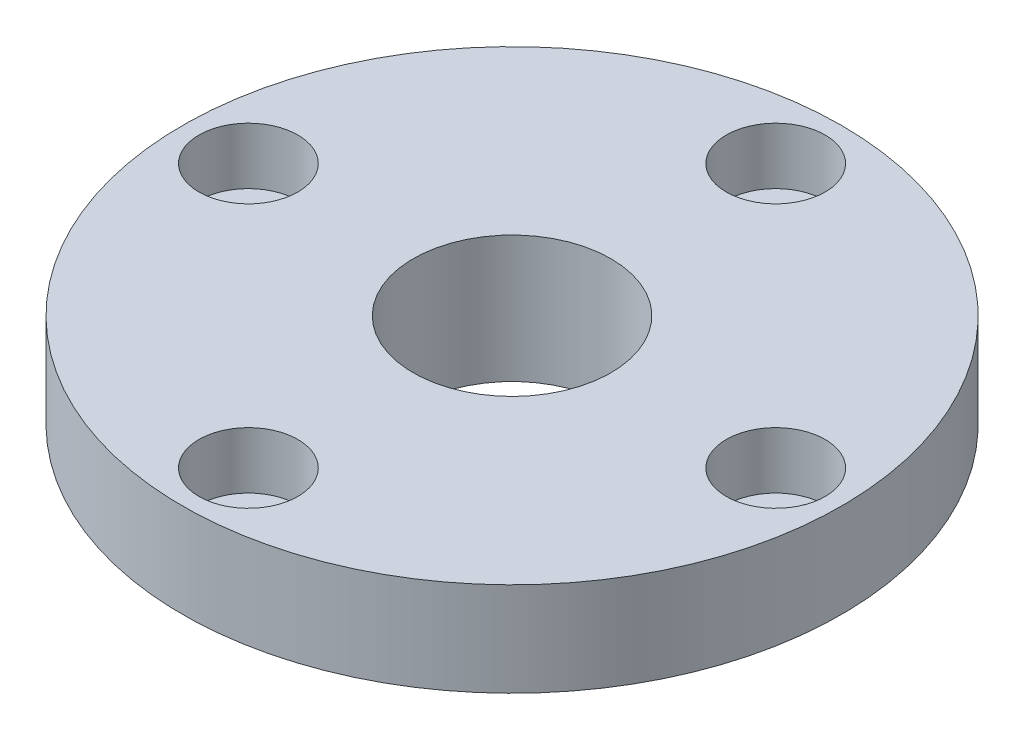
SolidWorks part; units mm, degrees
ref_plane "Płaszczyzna przednia" through (0, 0, 0) normal (0, 0, 1) x (1, 0, 0)
ref_plane "Płaszczyzna górna" through (0, 0, 0) normal (0, 1, 0) x (1, 0, 0)
ref_plane "Płaszczyzna prawa" through (0, 0, 0) normal (1, 0, 0) x (0, 0, -1)
sketch "Szkic1" plane through (0, 0, 0) normal (0, 0, 1) x (1, 0, 0)
  line L0 (0, 0) -> (0, 12.5653) construction
  line L1 (-15, 20.5326) -> (-50, 20.5326)
  line L2 (-50, 20.5326) -> (-50, 6.2826)
  line L3 (-15, 1.2826) -> (-32.5, 1.2826)
  line L4 (-32.5, 1.2826) -> (-32.5, 6.2826)
  line L5 (-32.5, 6.2826) -> (-50, 6.2826)
  line L7 (-15, 20.5326) -> (-15, 1.2826)
  dimension "D1" = 15
  dimension "D2" = 50
  dimension "D3" = 14.25
  dimension "D4" = 5
  dimension "D5" = 32.5
revolve "Obrót1" add sketch "Szkic1" angle 360 about L0
sketch "Szkic2" plane through (0, 20.5326, 0) normal (0, 1, 0) x (1, 0, 0)
  circle A0 centre (0, 0) radius 40
  point P3 (0, -40)
  point P4 (-40, 0)
  point P5 (0, 40)
  point P6 (40, 0)
hole_wizard "Pogłębienie walcowe pod M8 Wkręt z łbem walcowym z gniazdem sześciokątnym1" positions "Szkic 3D1" profile "Szkic3" counterbore size "M8" standard "ISO"
sketch3d "Szkic 3D1"
  point P0 (-40, 20.5326, 0)
  point P3 (0, 20.5326, -40)
  point P6 (40, 20.5326, 0)
  point P9 (0, 20.5326, 40)
sketch "Szkic3" plane through (-40, 20.5326, 0) normal (1, 0, 0) x (0, 0, 1)
  line L0 (0, 0) -> (0, 44.7039)
  line L1 (0, 44.7039) -> (4.5, 42)
  line L2 (4.5, 42) -> (4.5, 8.6)
  line L3 (4.5, 8.6) -> (7.5, 8.6)
  line L4 (7.5, 8.6) -> (7.5, 0)
  line L5 (7.5, 0) -> (0, 0)
  line L10 (0, 44.7039) -> (-4.5, 42) construction
  line L11 (0, -6.35) -> (0, 107.95) construction
  dimension "Średnica otworu" = 9
  dimension "Głębokość otworu" = 42
  dimension "Średnica pogłębienia walcowego" = 15
  dimension "Głębokość pogłębienia walcowego" = 8.6
  dimension "Kąt wiertła" = 118
